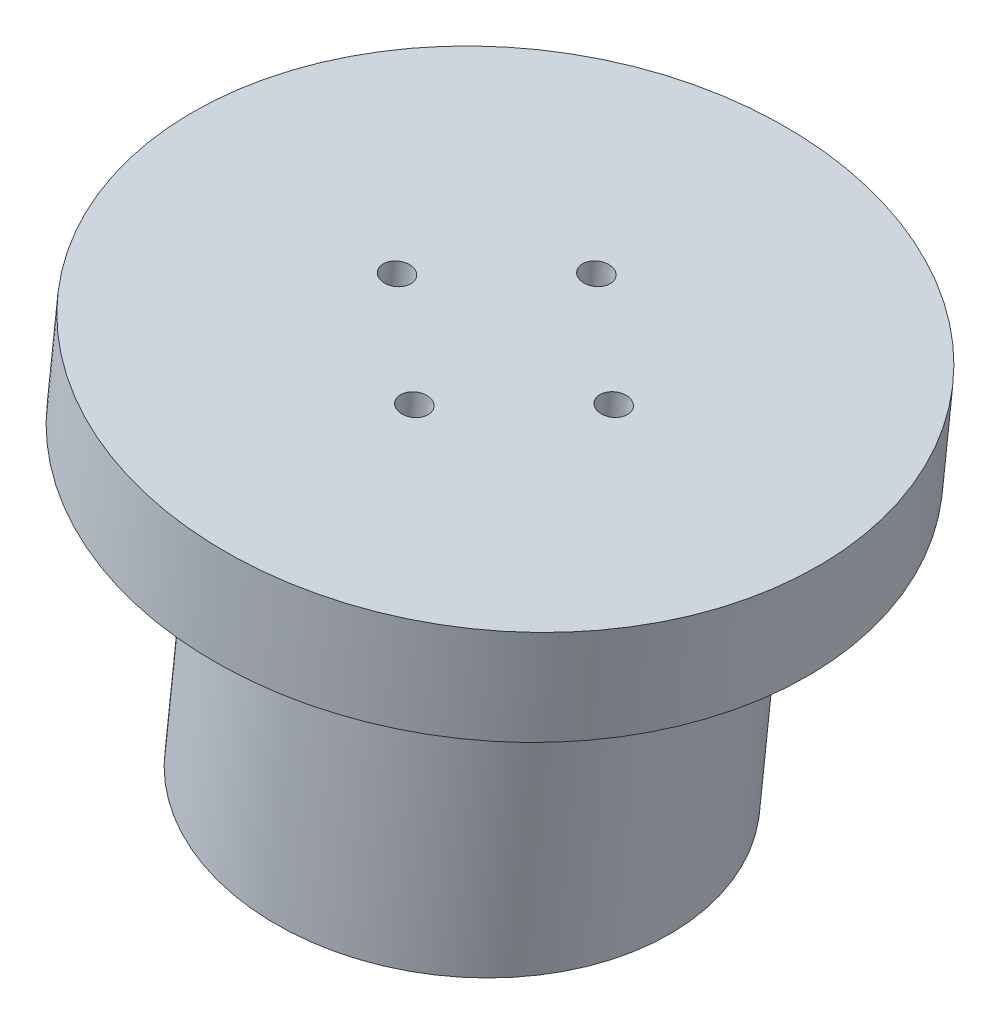
SolidWorks part; units mm, degrees
ref_plane "Front Plane" through (0, 0, 0) normal (0, 0, 1) x (1, 0, 0)
ref_plane "Top Plane" through (0, 0, 0) normal (0, 1, 0) x (1, 0, 0)
ref_plane "Right Plane" through (0, 0, 0) normal (1, 0, 0) x (0, 0, -1)
sketch "Sketch3" plane through (53.1324, 452.3468, 5.6226) normal (-0.1166, -0.9931, -0.0123) x (0.9932, -0.1166, -0.0014)
  circle A0 centre (-41.4274, 23.5307) radius 20.5995 construction
  circle A1 centre (-41.4274, 23.5307) radius 20.5995
extrude "Boss-Extrude2" add sketch "Sketch3" along normal up to surface (12 mm away) and the other way up to surface (18.35 mm away)
sketch "Sketch4" plane through (51.7327, 440.4296, 5.4744) normal (-0.1166, -0.9931, -0.0123) x (0.9932, -0.1166, -0.0014)
  line L0 (-38.552, 22.6751) -> (-41.0974, 20.5489)
  arc A0 (-38.552, 22.6751) -> (-43.3506, 25.8332) centre (-41.4274, 23.5307) ccw construction
  arc A1 (-43.3506, 25.8332) -> (-41.0974, 20.5489) centre (-41.4274, 23.5307) ccw construction
  arc A2 (-38.552, 22.6751) -> (-43.3506, 25.8332) centre (-41.4274, 23.5307) ccw
  arc A3 (-43.3506, 25.8332) -> (-41.0974, 20.5489) centre (-41.4274, 23.5307) ccw
extrude "Cut-Extrude2" cut sketch "Sketch4" against normal blind 10 contours A3 L0 A2
sketch "Sketch5" plane through (55.2729, 470.5701, 5.8491) normal (0.1166, 0.9931, 0.0123) x (0.9932, -0.1166, -0.0014)
  circle A0 centre (-41.4274, -23.5307) radius 31 construction
  circle A1 centre (-41.4274, -23.5307) radius 31
extrude "Boss-Extrude3" add sketch "Sketch5" along normal blind 10
sketch "Sketch7" plane through (56.4394, 480.5011, 5.9725) normal (0.1166, 0.9931, 0.0123) x (0.9932, -0.1166, -0.0014)
  circle A0 centre (-40.5533, -33.2706) radius 1.365
  arc A1 (-39.4297, -31.9255) -> (-41.6768, -34.6157) centre (-40.5533, -33.2706) ccw construction
  circle A2 centre (-51.1672, -24.4048) radius 1.365
  arc A3 (-52.1996, -25.8211) -> (-50.0437, -23.0598) centre (-51.1672, -24.4048) ccw construction
  circle A4 centre (-42.3015, -13.7909) radius 1.365
  circle A5 centre (-31.6875, -22.6566) radius 1.365
  arc A6 (-32.8111, -24.0017) -> (-30.564, -21.3115) centre (-31.6875, -22.6566) ccw construction
  arc A7 (-43.4251, -15.136) -> (-41.178, -12.4458) centre (-42.3015, -13.7909) ccw construction
  point P14 (-44.6591, -16.7658)
  dimension "D1" = 2.73
extrude "Cut-Extrude3" cut sketch "Sketch7" against normal up to next
